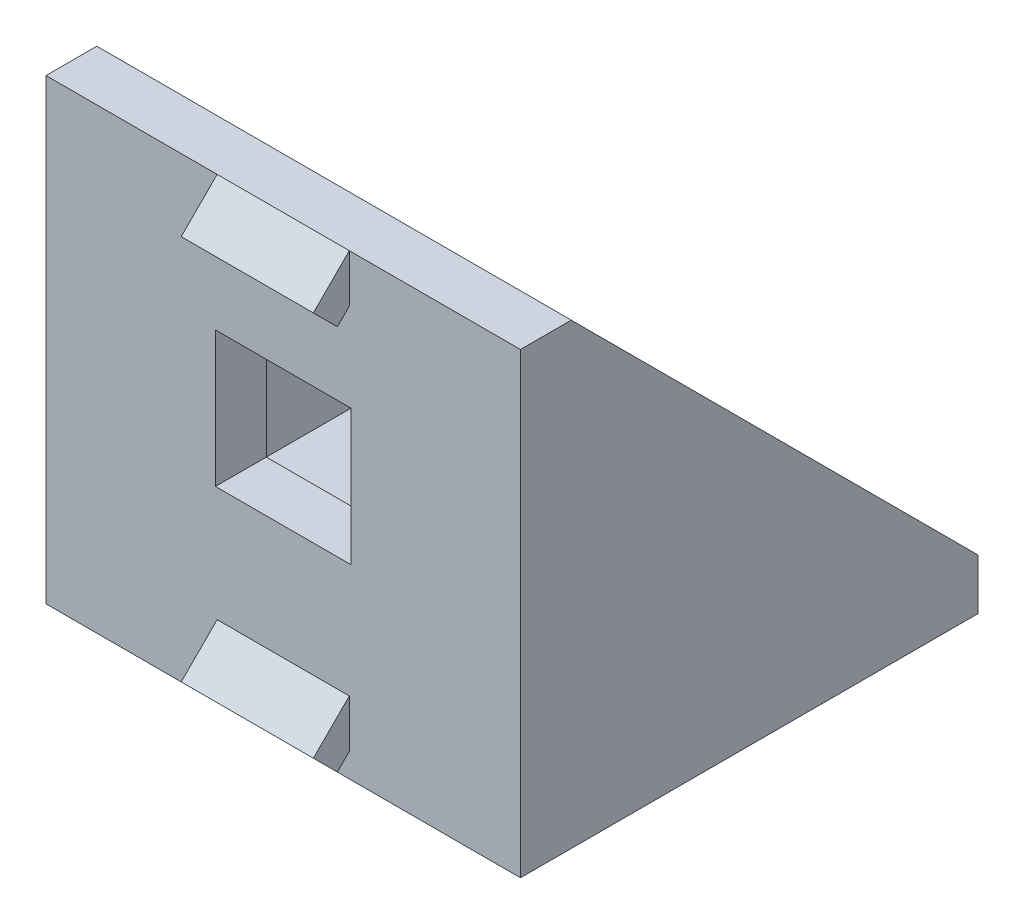
SolidWorks part; units mm, degrees
ref_plane "Front Plane" through (0, 0, 0) normal (0, 0, 1) x (1, 0, 0)
ref_plane "Top Plane" through (0, 0, 0) normal (0, 1, 0) x (1, 0, 0)
ref_plane "Right Plane" through (0, 0, 0) normal (1, 0, 0) x (0, 0, -1)
sketch "Sketch1" plane through (0, 0, 0) normal (1, 0, 0) x (0, 0, -1)
  line L0 (0, 0) -> (0, 27)
  line L1 (0, 0) -> (27, 0)
  line L2 (0, 27) -> (3, 27)
  line L3 (3, 27) -> (27, 3)
  line L4 (27, 3) -> (27, 0)
  dimension "D1" = 27
  dimension "D2" = 27
  dimension "D3" = 3
  dimension "D4" = 3
extrude "Boss-Extrude1" add sketch "Sketch1" along normal blind 28
sketch "Sketch2" plane through (0, 0, -27) normal (0, 0, -1) x (-1, 0, 0)
  line L0 (-28, 3) -> (0, 3) construction
  line L1 (-2, 3) -> (-26, 3)
  line L2 (-2, 3) -> (-2, 27)
  line L3 (-2, 27) -> (-26, 27)
  line L4 (-26, 3) -> (-26, 27)
  line L5 (-28, 27) -> (0, 27) construction
  line L6 (-28, 3) -> (-28, 27) construction
  line L7 (0, 3) -> (0, 27) construction
  dimension "D1" = 2
  dimension "D2" = 2
extrude "Cut-Extrude1" cut sketch "Sketch2" against normal offset from surface (24 mm away) 3 up to face at (14, 13.5, 0)
sketch "Sketch3" plane through (0, 0, -3) normal (0, 0, -1) x (-1, 0, 0)
  line L0 (-26, 27) -> (-2, 27) construction
  line L1 (-10, 19) -> (-18, 19)
  line L2 (-10, 19) -> (-10, 11)
  line L3 (-10, 11) -> (-18, 11)
  line L4 (-18, 19) -> (-18, 11)
  line L5 (-2, 3) -> (-26, 3) construction
  line L6 (-2, 27) -> (-2, 3) construction
  line L7 (-26, 3) -> (-26, 27) construction
  dimension "D1" = 8
  dimension "D2" = 8
  dimension "D3" = 8
  dimension "D4" = 8
extrude "Cut-Extrude2" cut sketch "Sketch3" against normal up to next
sketch "Sketch4" plane through (0, 3, 0) normal (0, 1, 0) x (1, 0, 0)
  line L0 (2, 3) -> (26, 3) construction
  line L1 (10, 11) -> (18, 11)
  line L2 (10, 11) -> (10, 19)
  line L3 (10, 19) -> (18, 19)
  line L4 (18, 11) -> (18, 19)
  line L5 (26, 27) -> (2, 27) construction
  line L6 (2, 3) -> (2, 27) construction
  line L7 (26, 3) -> (26, 27) construction
  dimension "D1" = 8
  dimension "D2" = 8
  dimension "8" = 8
  dimension "D3" = 8
extrude "Cut-Extrude3" cut sketch "Sketch4" against normal up to next
ref_plane "Plane1" through (14, 0, 0) normal (1, 0, 0) x (0, 0, -1)
sketch "Sketch5" plane through (14, 0, 0) normal (1, 0, 0) x (0, 0, -1)
  line L0 (27, 0) -> (24.8787, -2.1213)
  line L1 (24.8787, -2.1213) -> (23.4645, -0.7071)
  line L2 (23.4645, -0.7071) -> (24.1716, 0)
  line L3 (0, 0) -> (27, 0) construction
  line L4 (2.1213, -2.1213) -> (0.7071, -0.7071)
  line L5 (4.2426, 0) -> (2.1213, -2.1213)
  line L6 (0.7071, -0.7071) -> (1.4142, 0)
  line L7 (0, 27) -> (0, 0) construction
  line L8 (0, 1.4142) -> (-0.7071, 0.7071)
  line L9 (-0.7071, 0.7071) -> (-2.1213, 2.1213)
  line L10 (-2.1213, 2.1213) -> (0, 4.2426)
  line L11 (-0.7071, 23.4645) -> (-2.1213, 24.8787)
  line L12 (-2.1213, 24.8787) -> (0, 27)
  line L13 (0, 24.1716) -> (-0.7071, 23.4645)
  line L14 (24.1716, 0) -> (27, 0)
  line L15 (1.4142, 0) -> (4.2426, 0)
  line L16 (0, 1.4142) -> (0, 4.2426)
  line L17 (0, 27) -> (0, 24.1716)
  dimension "D1" = 3
  dimension "D2" = 2
  dimension "D3" = 45
  dimension "D4" = 1
  dimension "D5" = 3
  dimension "D6" = 45
  dimension "D7" = 2
  dimension "D8" = 3
  dimension "D9" = 1
  dimension "D10" = 45
  dimension "D11" = 3
  dimension "D12" = 1
  dimension "D13" = 2
  dimension "D14" = 45
extrude "Boss-Extrude2" add sketch "Sketch5" along normal mid plane 7.8
